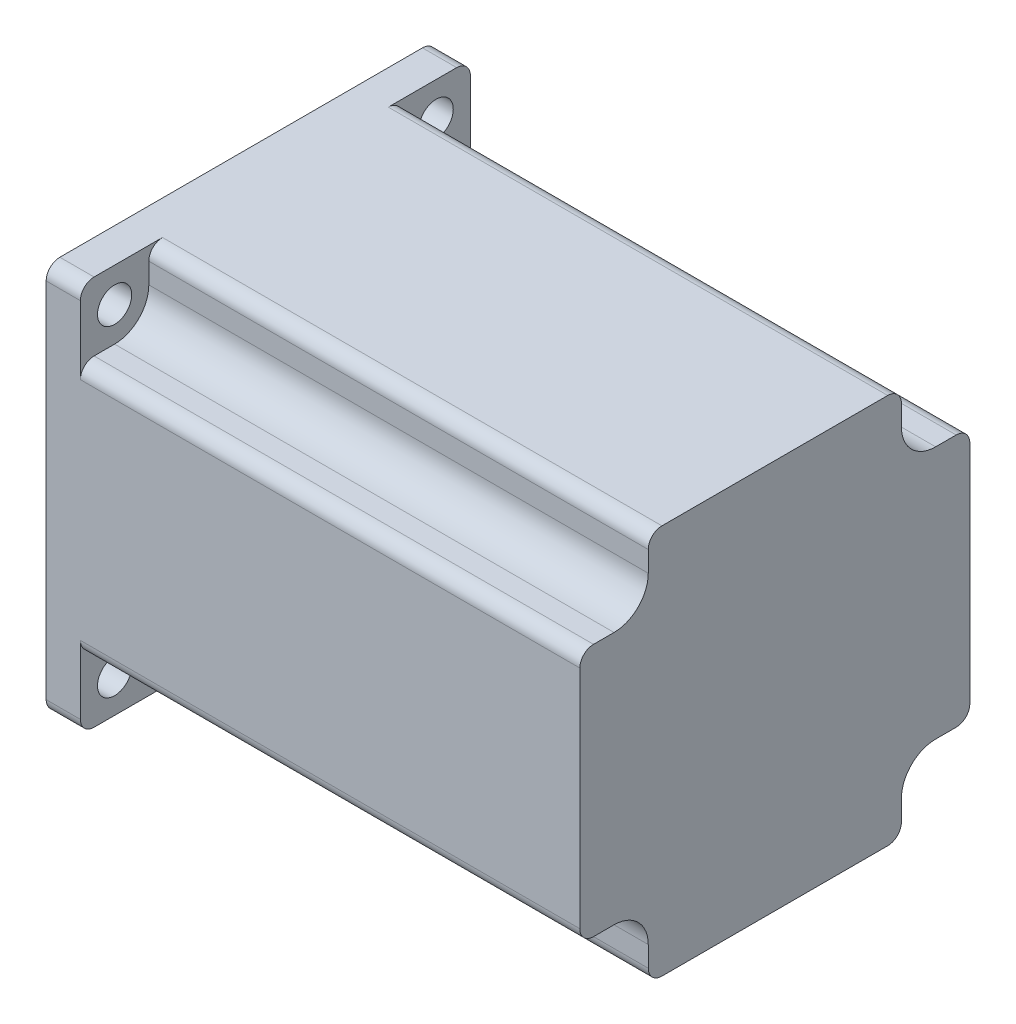
SolidWorks part; units mm, degrees
ref_plane "Front Plane" through (0, 0, 0) normal (0, 0, 1) x (1, 0, 0)
ref_plane "Top Plane" through (0, 0, 0) normal (0, 1, 0) x (1, 0, 0)
ref_plane "Right Plane" through (0, 0, 0) normal (1, 0, 0) x (0, 0, -1)
sketch "Sketch1" plane through (0, 0, 0) normal (1, 0, 0) x (0, 0, -1)
  line L0 (28.5, 0) -> (28.5, -57) construction
  line L1 (2, 0) -> (55, 0)
  line L2 (0, -2) -> (0, -55)
  line L3 (2, -57) -> (55, -57)
  line L4 (57, -2) -> (57, -55)
  line L5 (57, -28.5) -> (0, -28.5) construction
  arc A0 (0, -55) -> (2, -57) centre (2, -55) ccw
  arc A1 (55, -57) -> (57, -55) centre (55, -55) ccw
  arc A2 (55, 0) -> (57, -2) centre (55, -2) cw
  arc A3 (2, 0) -> (0, -2) centre (2, -2) ccw
  circle A4 centre (52, -5) radius 2.5
  circle A5 centre (52, -52) radius 2.5
  circle A6 centre (5, -52) radius 2.5
  circle A7 centre (5, -5) radius 2.5
  point P9 (57, -57)
  point P12 (57, 0)
  point P15 (0, 0)
  dimension "D3" = 2
  dimension "D4" = 5
  dimension "D7" = 5
  dimension "D1" = 57
  dimension "D2" = 57
  dimension "D5" = 47
  dimension "D6" = 47
extrude "Boss-Extrude2" add sketch "Sketch1" along normal blind 78
sketch "Sketch4" plane through (78, 0, 0) normal (1, 0, 0) x (0, 0, -1)
  line L1 (55, 0) -> (2, 0) construction
  line L2 (57, -55) -> (57, -2) construction
  line L3 (0, -2) -> (0, -55) construction
  line L5 (55, 0) -> (47, 0)
  line L6 (57, -10) -> (57, -2)
  line L7 (0, -2) -> (0, -10)
  line L8 (10, 0) -> (2, 0)
  line L11 (0, -10) -> (10, -10)
  line L12 (10, 0) -> (10, -10)
  line L14 (47, 0) -> (47, -10)
  line L15 (47, -10) -> (57, -10)
  arc A2 (2, 0) -> (0, -2) centre (2, -2) ccw construction
  arc A3 (57, -2) -> (55, 0) centre (55, -2) ccw construction
  arc A6 (2, 0) -> (0, -2) centre (2, -2) ccw
  arc A7 (57, -2) -> (55, 0) centre (55, -2) ccw
  dimension "D1" = 10
  dimension "D2" = 10
  dimension "D3" = 10
  dimension "D4" = 10
extrude "Cut-Extrude1" cut sketch "Sketch4" against normal blind 73
ref_plane "Plane1" through (0, -28.5, 0) normal (0, 1, 0) x (1, 0, 0)
fillet "Fillet1" radius 5 2 edges at (41.5, -10, -10) (41.5, -10, -47)
fillet "Fillet2" radius 2 4 edges at (41.5, 0, -10) (41.5, -10, 0) (41.5, -10, -57) (41.5, 0, -47)
mirror "Mirror3" about plane through (0, -28.5, 0) normal (0, 1, 0) of "Fillet1", "Cut-Extrude1"
fillet "Fillet3" radius 2 4 edges at (41.5, -47, -57) (41.5, -57, -47) (41.5, -47, 0) (41.5, -57, -10)
sketch "Sketch5" plane through (0, 0, 0) normal (-1, 0, 0) x (0, 0, 1)
  line L0 (-28.5, -57) -> (-28.5, 0) construction
  line L1 (-2, -57) -> (-55, -57) construction
  line L2 (-55, 0) -> (-2, 0) construction
  circle A0 centre (-28.5, -28.5) radius 19.5
  dimension "D1" = 39
extrude "Boss-Extrude3" add sketch "Sketch5" along normal blind 2
sketch "Sketch6" plane through (-2, 0, 0) normal (-1, 0, 0) x (0, 0, 1)
  line L0 (-28.5, -48) -> (-28.5, -9) construction
  circle A0 centre (-28.5, -28.5) radius 19.5 construction
  circle A1 centre (-28.5, -28.5) radius 19.5 construction
  circle A2 centre (-28.5, -28.5) radius 4
  dimension "D1" = 8
extrude "Boss-Extrude4" add sketch "Sketch6" along normal blind 20
